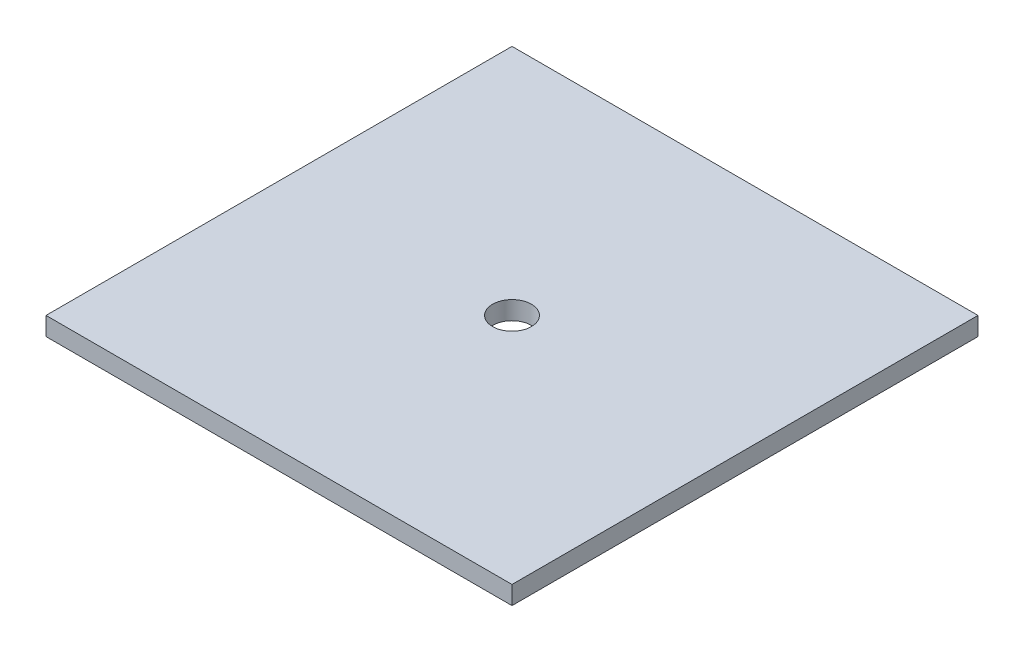
SolidWorks part; units mm, degrees
material "Maple"
ref_plane "Front Plane" through (0, 0, 0) normal (0, 0, 1) x (1, 0, 0)
ref_plane "Top Plane" through (0, 0, 0) normal (0, 1, 0) x (1, 0, 0)
ref_plane "Right Plane" through (0, 0, 0) normal (1, 0, 0) x (0, 0, -1)
sketch "Sketch1" plane through (0, 0, 0) normal (0, 1, 0) x (1, 0, 0)
  line L1 (-38.1, -38.1) -> (38.1, -38.1)
  line L2 (-38.1, -38.1) -> (-38.1, 38.1)
  line L3 (-38.1, 38.1) -> (38.1, 38.1)
  line L4 (38.1, -38.1) -> (38.1, 38.1)
  line L5 (-38.1, -38.1) -> (38.1, 38.1) construction
  line L6 (-38.1, 38.1) -> (38.1, -38.1) construction
  circle A0 centre (0, 0) radius 3.175
  circle A1 centre (31.7308, -31.7308) radius 5
  circle A2 centre (-31.7308, -31.7308) radius 5
  circle A3 centre (-31.7308, 31.7308) radius 5
  circle A4 centre (31.7308, 31.7308) radius 5
  point P0 (0, 0)
  point P19 (0, 0)
  dimension "D2" = 6.35
  dimension "D3" = 10
  dimension "D1" = 76.2
  dimension "D4" = 4
extrude "Boss-Extrude1" add sketch "Sketch1" along normal blind 3 contours A2 | A1 | A4 | A3 | L1 L4 L3 L2 A4 A3 A2 A1 A0
